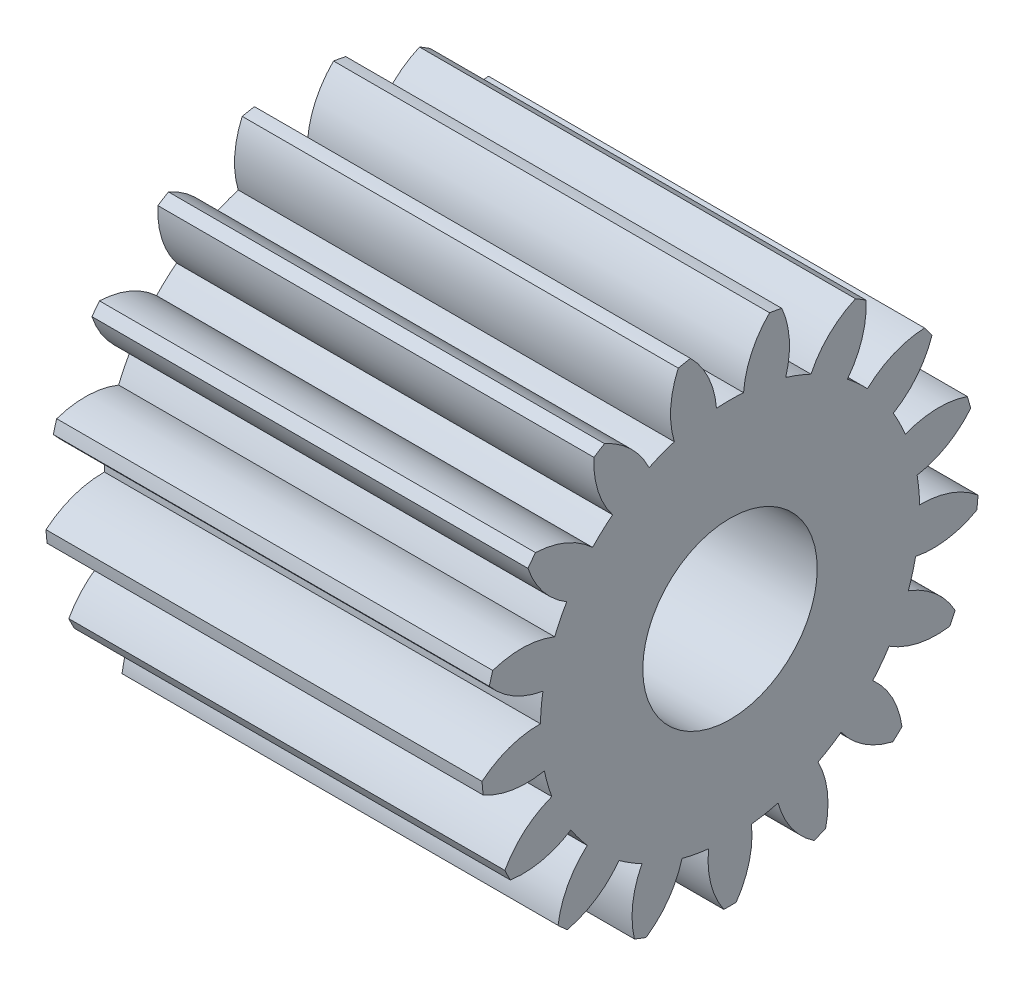
SolidWorks part; units mm, degrees
ref_plane "Plane1" through (0, 0, 0) normal (0, 0, 1) x (1, 0, 0)
ref_plane "Plane2" through (0, 0, 0) normal (0, 1, 0) x (1, 0, 0)
ref_plane "Plane3" through (0, 0, 0) normal (1, 0, 0) x (0, 0, -1)
sketch "HoldingSke" plane through (0, 0, 0) normal (0, 1, 0) x (1, 0, 0)
  line L0 (0, 0) -> (1.5938, -0.4873)
  line L1 (-15, 0) -> (100, 0) construction
  line L2 (0, 0) -> (-2.1039, 2.3779)
  line L3 (0, 0) -> (-11.863, 4.5341)
  line L4 (0, 0) -> (8.2586, 2.5249)
  line L5 (0, 0) -> (-46.8476, -17.4728)
  line L6 (0, 0) -> (-8.2896, -5.593)
  line L7 (-2.1039, 2.3779) -> (8.6586, 51.2059)
  line L8 (-76.2, 54.61) -> (-75.5, 54.61)
  line L9 (-71.009, 38.7566) -> (-53.1078, 45.2721)
  line L10 (-76.2, 71.12) -> (104.1128, 71.12)
  line L11 (0, 0) -> (-10, 0)
  line L12 (-76.2, 101.6) -> (-76.177, 101.6)
  line L13 (24.9733, 27.94) -> (52.9518, 28.4284)
  line L14 (24.9733, 27.94) -> (24.9743, 27.94)
  line L15 (24.9733, 27.94) -> (100.4006, 29.5858)
  line L16 (-63.627, -0.6) -> (-12.827, -0.6)
  circle A0 centre (0, 0) radius 2
  circle A1 centre (0, 0) radius 4.349
  circle A2 centre (0, 0) radius 37.5
  circle A3 centre (0, 0) radius 2
  dimension "MHD" = 8.698
  dimension "Hub_dia" = 75
  dimension "Bore" = 4
  dimension "MBD" = 4
  dimension "Num_teeth" = 17
  dimension "Pitch" = 1.6667
  dimension "Overall_len" = 50
  dimension "Show_teeth" = 17
  dimension "Thickness" = 10
  dimension "OAL" = 50.0001
  dimension "T_dim" = 0.7
  dimension "Ap" = 20
  dimension "H" = 19.05
  dimension "Pitch_radius" = 180.3128
  dimension "Width" = 10
  dimension "Backlash" = 0.023
  dimension "Addendum_fac" = 1
  dimension "Dedendum_fac" = 1.25
  dimension "Clearance_fac" = 0.25
  dimension "Dedendum_add" = 0.001
  dimension "Module" = 0.6
sketch "BasProSke" plane through (0, 0, 0) normal (0, 1, 0) x (1, 0, 0)
  line L0 (-10, 0) -> (60, 0) construction
  line L1 (0, 0) -> (0, 5.7)
  line L2 (0, 0) -> (10, 0)
  line L3 (10, 0) -> (10, 5.7)
  line L4 (10, 5.7) -> (0, 5.7)
  dimension "Thickness" = 10
  dimension "Diameter" = 11.4
revolve "Base-Revolve" add sketch "BasProSke" angle 360 about L0
sketch "TooCutSke" plane through (0, 0, 0) normal (1, 0, 0) x (0, 0, -1)
  line L1 (0, 0) -> (0, 107) construction
  line L2 (0, 0) -> (-0.5108, 5.0744) construction
  line L3 (0, 0) -> (-1.8676, 9.9906) construction
  line L4 (-0.5108, 5.0744) -> (-0.9338, 4.9953) construction
  arc A0 (0.3104, 4.3379) -> (-0.3104, 4.3379) centre (0, 0) ccw
  arc A1 (0.9293, 5.6495) -> (-0.9293, 5.6495) centre (0, 0) ccw
  circle A2 centre (0, 0) radius 5.1 construction
  circle A3 centre (0, 0) radius 4.7924 construction
  arc A4 (-0.3104, 4.3379) -> (-0.9293, 5.6495) centre (-2.3443, 4.1799) ccw
  arc A5 (0.9293, 5.6495) -> (0.3104, 4.3379) centre (2.3443, 4.1799) ccw
  dimension "Root_dia" = 8.698
  dimension "Overcut_dia" = 11.4508
  dimension "Pitch_dia" = 10.2
  dimension "Base_dia" = 9.5849
  dimension "Flank_rad" = 2.04
  dimension "Half_ang" = 10.588
  dimension "Half_CT" = 0.4303
extrude "ToothCut" cut sketch "TooCutSke" along normal through all
fillet "Breaks" [suppressed] radius 0.012
fillet "RootFillets" [suppressed] radius 0.151
pattern_circular "TeethCuts" count 17 every 21.176 about axis through (-10, 0, 0) along (1, 0, 0) of "ToothCut", "RootFillets", "Breaks"
sketch "HubNeaOneSke" plane through (0, 0, 0) normal (-1, 0, 0) x (0, 0, 1)
  circle A0 centre (0, 0) radius 4.349
  dimension "Diameter" = 8.698
extrude "HubNearOne" [suppressed] add sketch "HubNeaOneSke" along normal blind 40.0001
sketch "HubNeaBotSke" plane through (0, 0, 0) normal (-1, 0, 0) x (0, 0, 1)
  circle A0 centre (0, 0) radius 4.349
  dimension "Diameter" = 8.698
extrude "HubNearBoth" [suppressed] add sketch "HubNeaBotSke" along normal blind 20
ref_plane "FarPln" through (10, 0, 0) normal (1, 0, 0) x (0, 0, -1)
sketch "HubFarSke" plane through (10, 0, 0) normal (1, 0, 0) x (0, 0, -1)
  circle A0 centre (0, 0) radius 4.349
  dimension "Diameter" = 8.698
extrude "HubFar" [suppressed] add sketch "HubFarSke" along normal blind 20
sketch "BorSke" plane through (0, 0, 0) normal (1, 0, 0) x (0, 0, -1)
  circle A0 centre (0, 0) radius 2
  dimension "Diameter" = 4
extrude "Bore" cut sketch "BorSke" along normal mid plane 100.0001
sketch "KeySke" plane through (0, 0, 0) normal (1, 0, 0) x (0, 0, -1)
  line L0 (-0.8, 0) -> (-0.8, 2.7)
  line L1 (-0.8, 2.7) -> (0.8, 2.7)
  line L2 (0.8, 2.7) -> (0.8, 0)
  line L3 (0, 0) -> (0, 34) construction
  line L4 (-0.8, 0) -> (0.8, 0)
  dimension "Offset" = 2.7
  dimension "Width" = 1.6
extrude "Keyway" [suppressed] cut sketch "KeySke" along normal mid plane 100.0001
pattern_circular "Keyway2" [suppressed] count 2 every 90 about axis through (-10, 0, 0) along (1, 0, 0)
equation "' \"Module@HoldingSke\" = 6.35"
equation "' \"Num_teeth@HoldingSke\" = 12"
equation "' \"Ap@HoldingSke\" =  20"
equation "' \"Ap@HoldingSke\" = 20"
equation "' \"Width@HoldingSke\" = 0.5 * 25.4"
equation "' \"Hub_dia@HoldingSke\"= 1 * 25.4"
equation "' \"Hub_dia@HoldingSke\" = 1 * 25.4"
equation "' \"Overall_len@HoldingSke\" = 1.0 * 25.4"
equation "' \"Bore@HoldingSke\" = 0.75 * 25.4"
equation "' \"T_dim@HoldingSke\" = 0.1 * 25.4"
equation "' \"Width@KeySke\" = 0.25 * 25.4"
equation "' \"Show_teeth@HoldingSke\" = 13"
equation "' \"Backlash@HoldingSke\" = 0.009 * 25.4"
equation "' \"Addendum_fac@HoldingSke\" = 1.0"
equation "' \"Dedendum_fac@HoldingSke\" = 1.25"
equation "' \"Dedendum_add@HoldingSke\" = 0.00005 * 25.4"
equation "' \"Clearance_fac@HoldingSke\" = 0.25"
equation "\"Pitch@HoldingSke\" = 1 / \"Module@HoldingSke\""
equation "\"Overcut_dia@TooCutSke\" = (\"Num_teeth@HoldingSke\" + 2 * \"Addendum_fac@HoldingSke\") / \"Pitch@HoldingSke\" + 0.002 * 25.4"
equation "\"Pitch_dia@TooCutSke\" = \"Num_teeth@HoldingSke\" / \"Pitch@HoldingSke\""
equation "\"Base_dia@TooCutSke\" = \"Num_teeth@HoldingSke\" / \"Pitch@HoldingSke\" * cos((\"Ap@HoldingSke\"  * 3.14159265 / 180))"
equation "\"Root_dia@TooCutSke\" = (\"Num_teeth@HoldingSke\" + 2) / \"Pitch@HoldingSke\" - 2 * (\"Addendum_fac@HoldingSke\" + \"Dedendum_fac@HoldingSke\") / \"Pitch@HoldingSke\" - \"Dedendum_add@HoldingSke\" * 2"
equation "\"Half_ang@TooCutSke\" = 180 / \"Num_teeth@HoldingSke\""
equation "\"Half_CT@TooCutSke\" = \"Num_teeth@HoldingSke\" / \"Pitch@HoldingSke\" * sin((3.14159265 / 2 / \"Num_teeth@HoldingSke\")) / 2 - 7 * \"Backlash@HoldingSke\" / 4"
equation "\"Flank_rad@TooCutSke\" = \"Num_teeth@HoldingSke\" / \"Pitch@HoldingSke\" / 5"
equation "\"Radius@RootFillets\" = \"Clearance_fac@HoldingSke\" / \"Pitch@HoldingSke\" + \"Dedendum_add@HoldingSke\""
equation "\"Break_rad@Breaks\" = 0.02 / \"Pitch@HoldingSke\""
equation "\"Thickness@HoldingSke\" = \"Width@HoldingSke\""
equation "\"OAL@HoldingSke\" = \"Thickness@HoldingSke\""
equation "\"MHD@HoldingSke\" = (\"Num_teeth@HoldingSke\" + 2) / \"Pitch@HoldingSke\" - 2 * (\"Addendum_fac@HoldingSke\" + \"Dedendum_fac@HoldingSke\")  / \"Pitch@HoldingSke\" - \"Dedendum_add@HoldingSke\" * 2"
equation "\"MBD@HoldingSke\" = (\"Num_teeth@HoldingSke\" + 2) / \"Pitch@HoldingSke\" - 2 * (\"Addendum_fac@HoldingSke\" + \"Dedendum_fac@HoldingSke\")  / \"Pitch@HoldingSke\" - \"Dedendum_add@HoldingSke\" * 2 - 0.002 * 25.4"
equation "\"MHD@HoldingSke\" = ((sgn( \"MHD@HoldingSke\" - \"Hub_dia@HoldingSke\" )-1)*( \"MHD@HoldingSke\" - \"Hub_dia@HoldingSke\" ))/-2+ \"Hub_dia@HoldingSke\""
equation "\"MBD@HoldingSke\" = ((sgn( \"MBD@HoldingSke\" - \"Bore@HoldingSke\" )-1)*( \"MBD@HoldingSke\" - \"Bore@HoldingSke\" ))/-2+ \"Bore@HoldingSke\""
equation "\"OAL@HoldingSke\" = ((sgn( \"OAL@HoldingSke\" - \"Overall_len@HoldingSke\" )+1)*( \"OAL@HoldingSke\" - \"Overall_len@HoldingSke\" ))/2 + \"Overall_len@HoldingSke\" + 0.000002 * 25.4"
equation "\"Num_teeth@TeethCuts\" = int( \"Show_teeth@HoldingSke\" ) + 1"
equation "\"Num_teeth@TeethCuts\" = ((sgn( \"Num_teeth@TeethCuts\" - \"Num_teeth@HoldingSke\" )-1)*( \"Num_teeth@TeethCuts\" - \"Num_teeth@HoldingSke\" ))/-2+ \"Num_teeth@HoldingSke\""
equation "\"Num_teeth@TeethCuts\" = ((sgn( \"Num_teeth@TeethCuts\" - 2.0)+1)*( \"Num_teeth@TeethCuts\" - 2.0))/2 +2.0"
equation "\"Angle@TeethCuts\" = 360.0 / \"Num_teeth@HoldingSke\""
equation "\"Diameter@BasProSke\" = (\"Num_teeth@HoldingSke\" + 2 * \"Addendum_fac@HoldingSke\") / \"Pitch@HoldingSke\""
equation "\"Thickness@BasProSke\"  = \"Thickness@HoldingSke\""
equation "' \"Fillet_rad@BasProSke\" =  \"Thickness@HoldingSke\" * 0.05"
equation "' \"Fillet_rad@BasProSke\" = \"Thickness@HoldingSke\" * 0.05"
equation "\"MHD@HoldingSke\" = ((sgn( \"MHD@HoldingSke\" - \"Root_dia@TooCutSke\" )-1)*( \"MHD@HoldingSke\" - \"Root_dia@TooCutSke\" ))/-2+ \"Root_dia@TooCutSke\""
equation "\"Diameter@HubNeaOneSke\" = \"MHD@HoldingSke\""
equation "\"Length@HubNearOne\" = \"OAL@HoldingSke\" - \"Thickness@BasProSke\""
equation "\"Diameter@HubNeaBotSke\" = \"MHD@HoldingSke\""
equation "\"Length@HubNearBoth\" = ( \"OAL@HoldingSke\" - \"Thickness@BasProSke\" ) / 2.0"
equation "\"Thickness@FarPln\" = \"Thickness@BasProSke\""
equation "\"Diameter@HubFarSke\" = \"MHD@HoldingSke\""
equation "\"Length@HubFar\" = ( \"OAL@HoldingSke\" - \"Thickness@BasProSke\" ) / 2.0"
equation "\"Diameter@BorSke\" = \"MBD@HoldingSke\""
equation "\"D1@Bore\" = \"OAL@HoldingSke\" * 2.0"
equation "\"D1@Keyway\" = \"OAL@HoldingSke\" * 2.0"
equation "\"Offset@KeySke\" = \"T_dim@HoldingSke\" + \"MBD@HoldingSke\" / 2.0"
